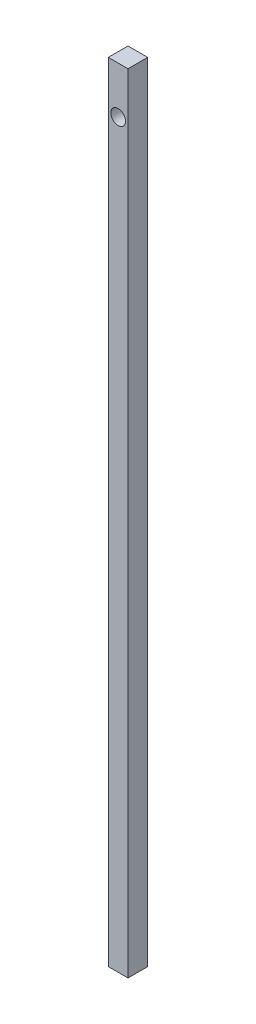
SolidWorks part; units mm, degrees
ref_plane "Front Plane" through (0, 0, 0) normal (0, 0, 1) x (1, 0, 0)
ref_plane "Top Plane" through (0, 0, 0) normal (0, 1, 0) x (1, 0, 0)
ref_plane "Right Plane" through (0, 0, 0) normal (1, 0, 0) x (0, 0, -1)
sketch "Sketch1" plane through (0, 0, 0) normal (0, 1, 0) x (1, 0, 0)
  line L1 (-25.4, -25.4) -> (25.4, -25.4)
  line L2 (-25.4, -25.4) -> (-25.4, 25.4)
  line L3 (-25.4, 25.4) -> (25.4, 25.4)
  line L4 (25.4, -25.4) -> (25.4, 25.4)
  line L5 (-25.4, -25.4) -> (25.4, 25.4) construction
  line L6 (-25.4, 25.4) -> (25.4, -25.4) construction
  point P0 (0, 0)
  dimension "D1" = 50.8
  dimension "D2" = 50.8
extrude "Boss-Extrude1" add sketch "Sketch1" along normal blind 2032
sketch "Sketch2" plane through (0, 0, 25.4) normal (0, 0, 1) x (1, 0, 0)
  line L1 (-25.4, 0) -> (25.4, 0) construction
  line L2 (25.4, 2032) -> (25.4, 0) construction
  circle A0 centre (0, 1911.35) radius 19.05
  point P2 (0, 1930.4)
  dimension "D1" = 38.1
  dimension "D2" = 1930.4
  dimension "D3" = 25.4
extrude "Cut-Extrude1" cut sketch "Sketch2" against normal through all
